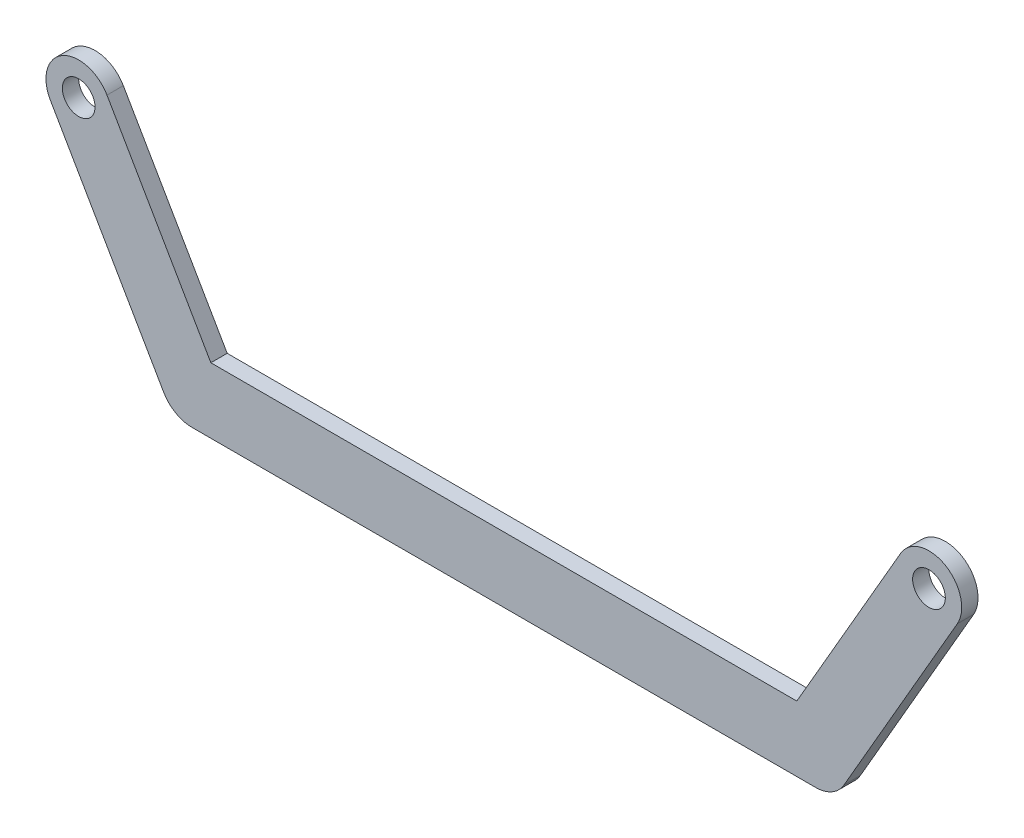
SolidWorks part; units mm, degrees
material "Plain Carbon Steel"
ref_plane "Front Plane" through (0, 0, 0) normal (0, 0, 1) x (1, 0, 0)
ref_plane "Top Plane" through (0, 0, 0) normal (0, 1, 0) x (1, 0, 0)
ref_plane "Right Plane" through (0, 0, 0) normal (1, 0, 0) x (0, 0, -1)
sketch "Sketch1" plane through (0, 0, 0) normal (0, 0, 1) x (1, 0, 0)
  line L0 (-605.5295, 0) -> (605.5295, 0) construction
  line L1 (-605.5295, 63.5) -> (605.5295, 63.5)
  line L2 (-605.5295, -63.5) -> (605.5295, -63.5)
  line L3 (605.5295, 0) -> (825.5, 381) construction
  line L4 (550.5369, 31.75) -> (770.5074, 412.75)
  line L5 (660.5222, -31.75) -> (880.4926, 349.25)
  line L6 (-605.5295, 0) -> (-825.5, 381) construction
  line L7 (-660.5222, -31.75) -> (-880.4926, 349.25)
  line L8 (-550.5369, 31.75) -> (-770.5074, 412.75)
  arc A0 (-605.5295, 63.5) -> (-605.5295, -63.5) centre (-605.5295, 0) ccw
  arc A1 (605.5295, -63.5) -> (605.5295, 63.5) centre (605.5295, 0) ccw
  arc A2 (550.5369, 31.75) -> (660.5222, -31.75) centre (605.5295, 0) ccw
  arc A3 (880.4926, 349.25) -> (770.5074, 412.75) centre (825.5, 381) ccw
  arc A4 (-660.5222, -31.75) -> (-550.5369, 31.75) centre (-605.5295, 0) ccw
  arc A5 (-770.5074, 412.75) -> (-880.4926, 349.25) centre (-825.5, 381) ccw
  point P2 (0, 0)
  point P10 (715.5148, 190.5)
  point P15 (-715.5148, 190.5)
  dimension "D1" = 63.5
  dimension "D2" = 63.5
  dimension "D3" = 63.5
  dimension "D4" = 381
  dimension "D5" = 381
  dimension "D6" = 120
  dimension "D7" = 120
  dimension "D8" = 1651
extrude "Boss-Extrude1" add sketch "Sketch1" against normal blind 31.75 contours L5 A3 L4 L1 A1 | L4 A2 A1 L1 | A4 L2 A2 L4 L1 L8 | A0 A4 L8 L1 | L8 A5 L7 A0 L1
sketch "Sketch2" plane through (0, 0, 0) normal (0, 0, 1) x (1, 0, 0)
  circle A0 centre (825.5, 381) radius 31.75
  circle A1 centre (-825.5, 381) radius 31.75
  dimension "D1" = 63.5
extrude "Cut-Extrude1" cut sketch "Sketch2" against normal through all
